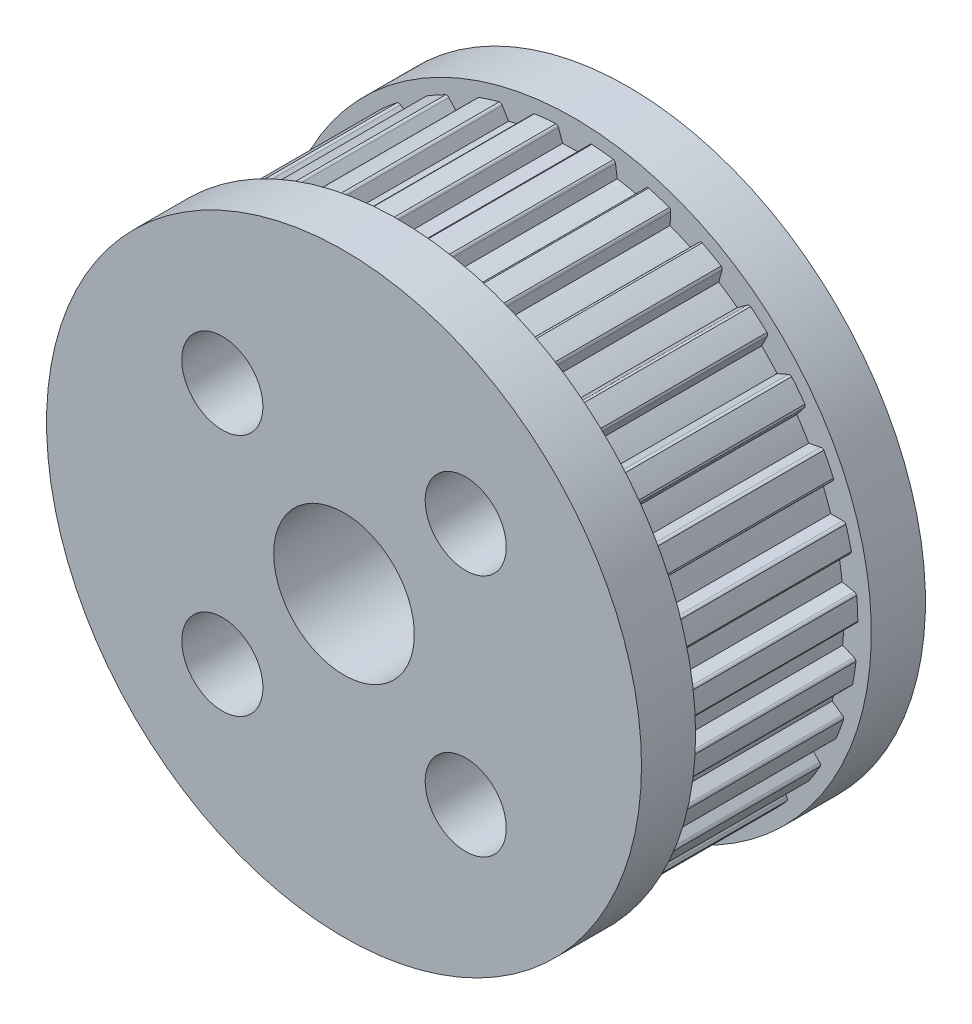
SolidWorks part; units mm, degrees
ref_plane "Plan de face" through (0, 0, 0) normal (0, 0, 1) x (1, 0, 0)
ref_plane "Plan de dessus" through (0, 0, 0) normal (0, 1, 0) x (1, 0, 0)
ref_plane "Plan de droite" through (0, 0, 0) normal (1, 0, 0) x (0, 0, -1)
sketch "Esquisse1" plane through (0, 0, 0) normal (0, 0, 1) x (1, 0, 0)
  line L0 (0, 0) -> (0, 11.7813) construction
  circle A0 centre (0, 0) radius 10.5
  dimension "D1" = 21
extrude "Boss.-Extru.1" add sketch "Esquisse1" along normal blind 6.5 contours A0
sketch "Esquisse2" plane through (0, 0, 6.5) normal (0, 0, 1) x (1, 0, 0)
  line L9 (0, 0) -> (0, 11.354) construction
  line L11 (-0.415, 9.9718) -> (-0.5707, 10.3994)
  line L12 (-0.6919, 10.4805) -> (-1.016, 10.4641)
  line L14 (0.415, 9.9718) -> (0.5707, 10.3994)
  line L15 (0.6919, 10.4805) -> (1.0144, 10.4641)
  line L16 (-1.016, 10.4641) -> (-1.016, 11.1126)
  line L17 (-1.016, 11.1126) -> (1.0144, 11.1126)
  line L18 (1.0144, 11.1126) -> (1.0144, 10.4641)
  line L22 (-0.415, 9.9718) -> (0.415, 9.9718) construction
  line L23 (-0.601, 10.4828) -> (-0.7038, 10.3321) construction
  circle A0 centre (0, 0) radius 10
  circle A1 centre (0, 0) radius 10.5 construction
  arc A2 (-0.415, 9.9718) -> (0.415, 9.9718) centre (0, 0) cw
  arc A5 (-0.5707, 10.3994) -> (-0.6919, 10.4805) centre (-0.6821, 10.364) ccw
  arc A6 (0.5707, 10.3994) -> (0.6919, 10.4805) centre (0.6821, 10.364) cw
  point P11 (0, 9.9718)
  point P19 (1.0144, 10.4641)
  point P20 (-1.016, 10.4641)
  dimension "D1" = 20
  dimension "D8" = 52.785
  dimension "D2" = 70
  dimension "D3" = 0.186
  dimension "D5" = 0.83
  dimension "D7" = 0.415
extrude "Enlèv. mat.-Extru.1" cut sketch "Esquisse2" against normal up to next contours L17 L18 L15 A6 L14 A2 L11 A5 L12 L16
pattern_circular "Répétition circulaire1" count 31 every 11.612 about axis through (0, 0, 0) along (0, 0, 1) of "Enlèv. mat.-Extru.1"
sketch "Esquisse3" plane through (0, 0, 6.5) normal (0, 0, 1) x (1, 0, 0)
  circle A0 centre (0, 0) radius 11
  dimension "D1" = 22
extrude "Boss.-Extru.2" add sketch "Esquisse3" along normal blind 2
sketch "Esquisse4" plane through (0, 0, 0) normal (0, 0, -1) x (-1, 0, 0)
  circle A0 centre (0, 0) radius 11
extrude "Boss.-Extru.3" add sketch "Esquisse4" along normal blind 2
sketch "Esquisse5" plane through (0, 0, -2) normal (0, 0, -1) x (-1, 0, 0)
  line L1 (-4.5, -4.5) -> (4.5, -4.5) construction
  line L2 (-4.5, -4.5) -> (-4.5, 4.5) construction
  line L3 (-4.5, 4.5) -> (4.5, 4.5) construction
  line L4 (4.5, -4.5) -> (4.5, 4.5) construction
  line L5 (-4.5, -4.5) -> (4.5, 4.5) construction
  line L6 (-4.5, 4.5) -> (4.5, -4.5) construction
  circle A0 centre (0, 0) radius 2.6
  circle A1 centre (-4.5, 4.5) radius 1.5
  circle A2 centre (-4.5, -4.5) radius 1.5
  circle A3 centre (4.5, -4.5) radius 1.5
  circle A4 centre (4.5, 4.5) radius 1.5
  dimension "D1" = 5.2
  dimension "D3" = 3
  dimension "D4" = 3
  dimension "D5" = 3
  dimension "D6" = 3
  dimension "D2" = 9
extrude "Enlèv. mat.-Extru.2" cut sketch "Esquisse5" against normal through all
sketch "Esquisse6" plane through (0, 0, -2) normal (0, 0, -1) x (-1, 0, 0)
  circle A0 centre (0, 0) radius 9.65
  dimension "D1" = 19.3
extrude "Enlèv. mat.-Extru.3" cut sketch "Esquisse6" against normal blind 5
